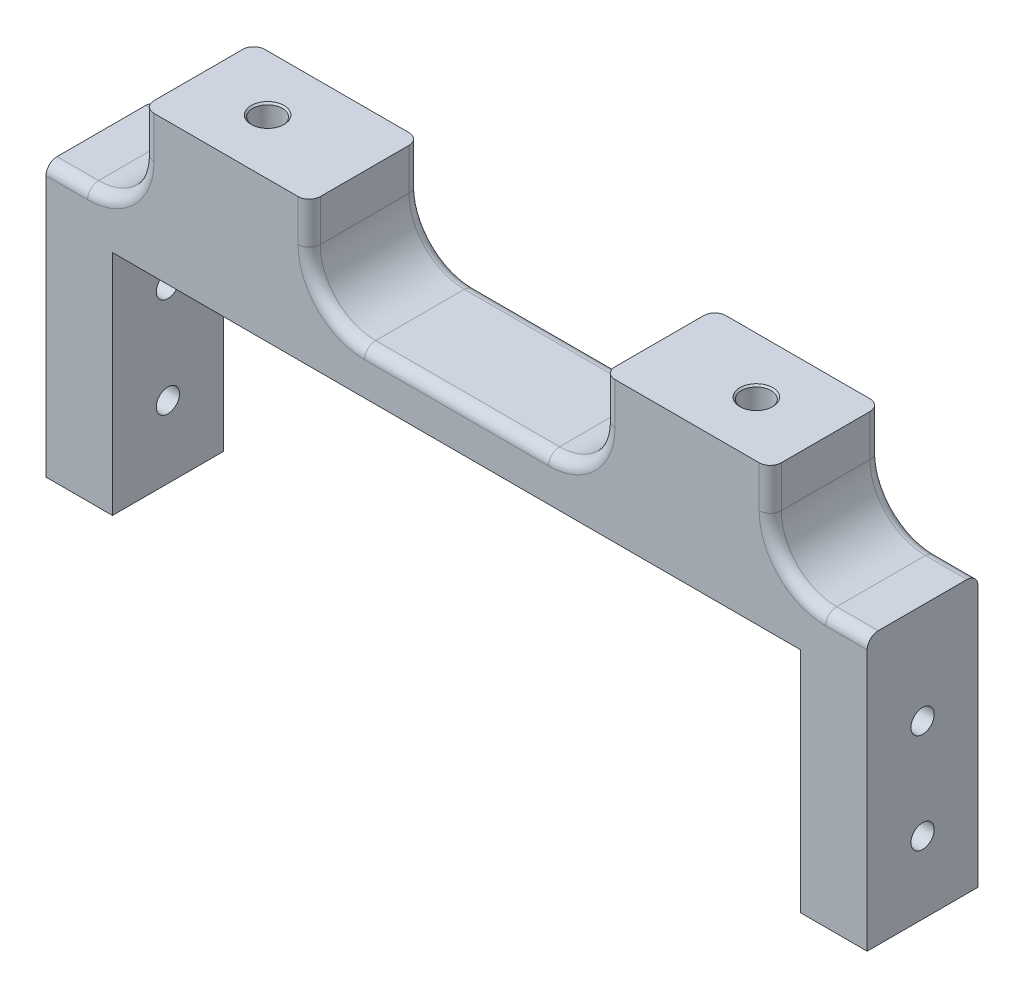
SolidWorks part; units mm, degrees
material "ABS"
ref_plane "Front Plane" through (0, 0, 0) normal (0, 0, 1) x (1, 0, 0)
ref_plane "Top Plane" through (0, 0, 0) normal (0, 1, 0) x (1, 0, 0)
ref_plane "Right Plane" through (0, 0, 0) normal (1, 0, 0) x (0, 0, -1)
sketch "Sketch1" plane through (0, 0, 0) normal (0, 0, 1) x (1, 0, 0)
  line L0 (62.1, -20.55) -> (74.1, -20.55)
  line L1 (-62.1, -20.55) -> (62.1, -20.55)
  line L2 (-62.1, -20.55) -> (-62.1, 20.55)
  line L3 (-62.1, 20.55) -> (62.1, 20.55)
  line L4 (62.1, -20.55) -> (62.1, 20.55)
  line L5 (-62.1, -20.55) -> (62.1, 20.55) construction
  line L6 (-62.1, 20.55) -> (62.1, -20.55) construction
  line L7 (74.1, -20.55) -> (74.1, 28.55)
  line L8 (74.1, 28.55) -> (-74.1, 28.55)
  line L9 (-74.1, 28.55) -> (-74.1, -20.55)
  line L10 (-74.1, -20.55) -> (-62.1, -20.55)
  point P0 (0, 0)
  dimension "D1" = 124.2
  dimension "D2" = 41.1
  dimension "D3" = 12
  dimension "D5" = 8
extrude "Boss-Extrude1" add sketch "Sketch1" along normal blind 20 contours L9 L10 L2 L3 L4 L0 L7 L8
sketch "Sketch2" plane through (-74.1, 0, 0) normal (-1, 0, 0) x (0, 0, 1)
  line L0 (20, -20.55) -> (0, -20.55) construction
  line L3 (0, 28.55) -> (0, -20.55) construction
  circle A0 centre (10, 10.45) radius 2.1
  circle A1 centre (10, -7.55) radius 2.1
  dimension "D1" = 4.2
  dimension "D2" = 18
  dimension "D3" = 13
  dimension "D4" = 10
extrude "Cut-Extrude1" cut sketch "Sketch2" against normal blind 149
sketch "Sketch3" plane through (0, 0, 20) normal (0, 0, 1) x (1, 0, 0)
  line L0 (-56.6, 28.55) -> (-56.6, 46.05)
  line L1 (74.1, 28.55) -> (-74.1, 28.55) construction
  line L2 (-56.6, 46.05) -> (-26.6, 46.05)
  line L3 (-26.6, 46.05) -> (-26.6, 28.55)
  line L4 (-26.6, 28.55) -> (-56.6, 28.55)
  line L5 (-74.1, 28.55) -> (-74.1, -20.55) construction
  dimension "D1" = 17.5
  dimension "D2" = 30
  dimension "D3" = 17.5
extrude "Boss-Extrude2" add sketch "Sketch3" against normal blind 20
fillet "Fillet1" radius 10 2 edges at (-26.6, 28.55, 10) (-56.6, 28.55, 10)
ref_plane "Plane1" through (0, 0, 0) normal (1, 0, 0) x (0, 0, -1)
mirror "Mirror1" about plane through (0, 0, 0) normal (1, 0, 0) of "Fillet1", "Boss-Extrude2"
fillet "Fillet2" radius 2 22 edges at (-56.6, 42.3, 0) (-59.5289, 31.4789, 0) (-59.5289, 31.4789, 20) (26.6, 42.3, 0) (26.6, 42.3, 20) (23.6711, 31.4789, 0) (23.6711, 31.4789, 20) (-26.6, 42.3, 0) (-23.6711, 31.4789, 0) (-23.6711, 31.4789, 20) (56.6, 42.3, 20) (56.6, 42.3, 0) (70.35, 28.55, 20) (70.35, 28.55, 0) (0, 28.55, 20) (0, 28.55, 0) (-26.6, 42.3, 20) (-56.6, 42.3, 20) (-70.35, 28.55, 20) (-70.35, 28.55, 0) (59.5289, 31.4789, 0) (59.5289, 31.4789, 20)
sketch "Sketch4" plane through (0, 46.05, 0) normal (0, 1, 0) x (1, 0, 0)
  line L0 (28.6, 0) -> (54.6, 0) construction
  line L1 (56.6, -2) -> (56.6, -18) construction
  line L2 (-28.6, 0) -> (-54.6, 0) construction
  line L3 (-56.6, -2) -> (-56.6, -18) construction
  circle A0 centre (44.1, -10) radius 2.675
  circle A1 centre (-44.1, -10) radius 2.675
  dimension "D1" = 10
  dimension "D3" = 5.35
  dimension "D4" = 10
  dimension "D6" = 5.35
  dimension "D2" = 12.5
  dimension "D5" = 12.5
extrude "Cut-Extrude2" cut sketch "Sketch4" against normal blind 7
chamfer "Chamfer1" distance 0.3 angle 45 2 edges at (41.425, 46.05, 10) (-46.775, 46.05, 10)
